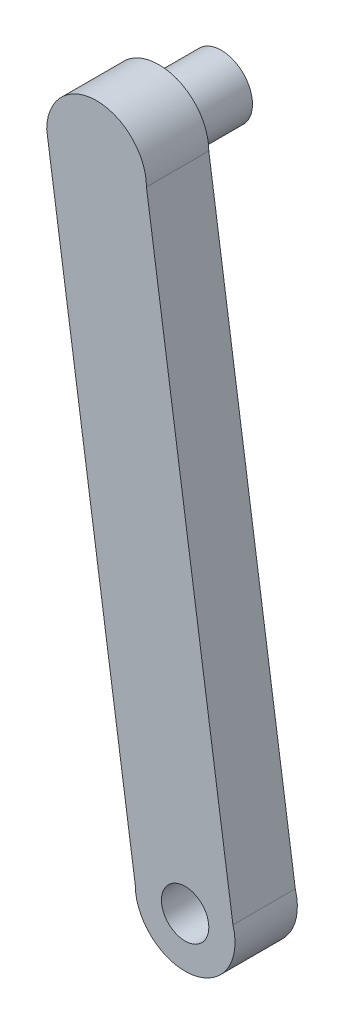
SolidWorks part; units mm, degrees
ref_plane "Front Plane" through (0, 0, 0) normal (0, 0, 1) x (1, 0, 0)
ref_plane "Top Plane" through (0, 0, 0) normal (0, 1, 0) x (1, 0, 0)
ref_plane "Right Plane" through (0, 0, 0) normal (1, 0, 0) x (0, 0, -1)
sketch "Sketch1" plane through (0, 0, 0) normal (0, 0, 1) x (1, 0, 0)
  line L0 (13.1, 0) -> (6, 48.9124)
  line L1 (20.9349, 1.1373) -> (14, 48.9124)
  circle A0 centre (17.1, 0) radius 1.9
  arc A1 (13.1, 0) -> (20.9349, 1.1373) centre (17.1, 0) ccw
  arc A2 (14, 48.9124) -> (6, 48.9124) centre (10, 48.9124) ccw
  dimension "D1" = 8
extrude "Boss-Extrude1" add sketch "Sketch1" along normal blind 5
sketch "Sketch2" plane through (0, 0, 0) normal (0, 0, -1) x (-1, 0, 0)
  circle A0 centre (-10, 48.9124) radius 2.5
  dimension "D1" = 5
extrude "Boss-Extrude2" add sketch "Sketch2" along normal blind 5
